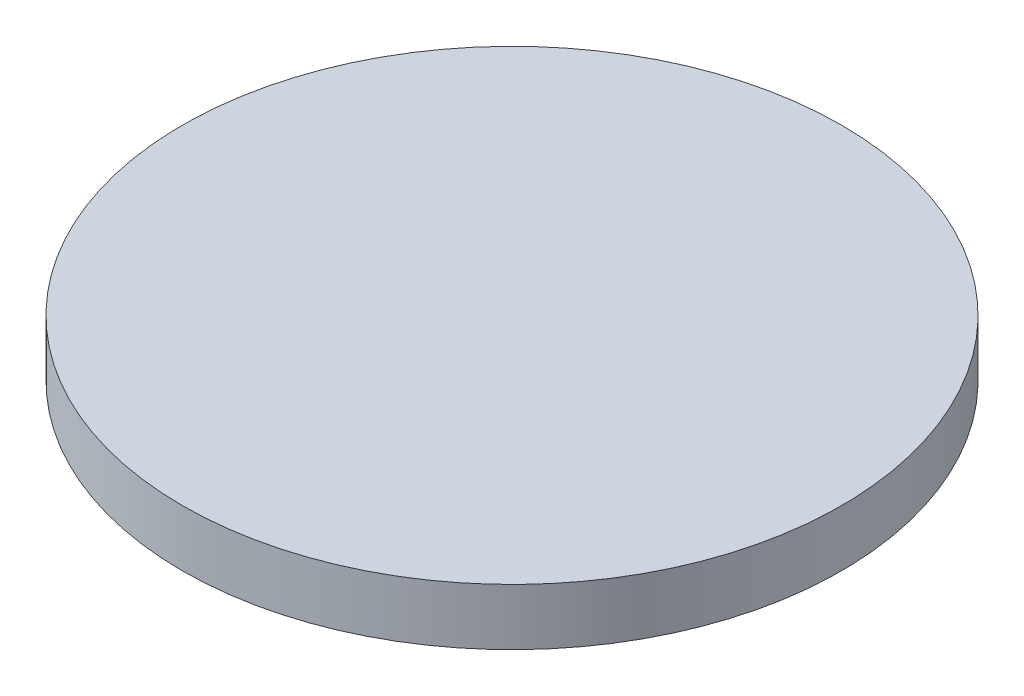
SolidWorks part; units mm, degrees
ref_plane "Front Plane" through (0, 0, 0) normal (0, 0, 1) x (1, 0, 0)
ref_plane "Top Plane" through (0, 0, 0) normal (0, 1, 0) x (1, 0, 0)
ref_plane "Right Plane" through (0, 0, 0) normal (1, 0, 0) x (0, 0, -1)
sketch "Sketch1" plane through (0, 0, 0) normal (0, 1, 0) x (1, 0, 0)
  circle A0 centre (0, 0) radius 4.445
  circle A1 centre (0, 0) radius 3.0383
  dimension "D1" = 8.89
extrude "Boss-Extrude1" add sketch "Sketch1" along normal blind 0.762 contours A1 | A0 A1
